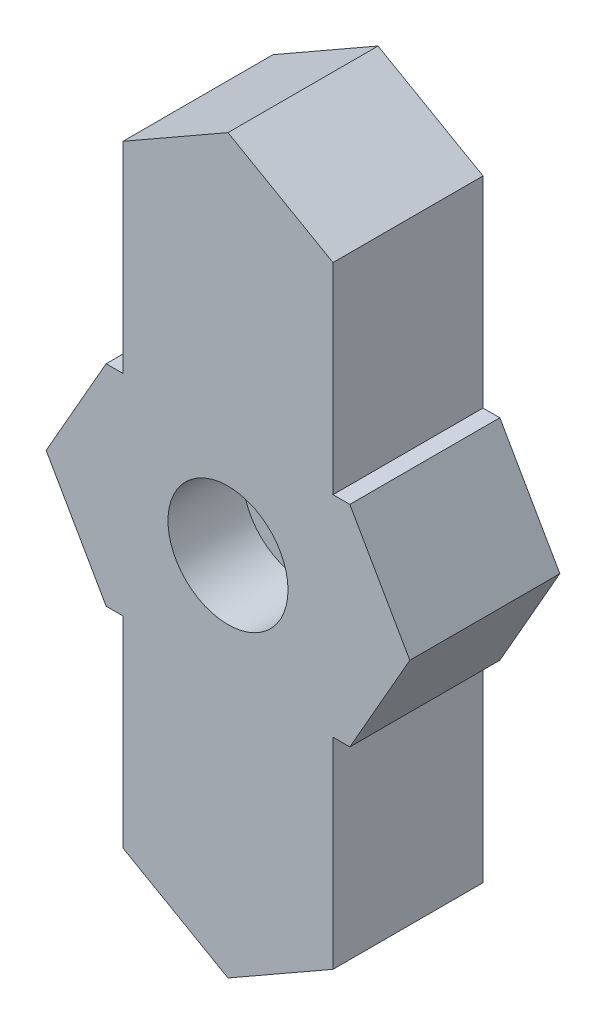
SolidWorks part; units mm, degrees
material "Plain Carbon Steel"
ref_plane "Front Plane" through (0, 0, 0) normal (0, 0, 1) x (1, 0, 0)
ref_plane "Top Plane" through (0, 0, 0) normal (0, 1, 0) x (1, 0, 0)
ref_plane "Right Plane" through (0, 0, 0) normal (1, 0, 0) x (0, 0, -1)
sketch "Sketch1" plane through (0, 0, 0) normal (0, 0, 1) x (1, 0, 0)
  line L0 (0, 0) -> (-15.3924, 0)
  line L8 (0, 30.988) -> (0, 0)
  line L9 (-15.3924, 0) -> (-10.3124, 8.89)
  line L10 (-10.3124, 8.89) -> (-8.89, 8.89)
  line L11 (0, 30.988) -> (-8.89, 25.908)
  line L12 (-8.89, 25.908) -> (-8.89, 8.89)
  point P3 (-7.6962, 0)
  dimension "D1" = 30.988
  dimension "D2" = 15.3924
  dimension "D3" = 8.89
  dimension "D6" = 8.89
extrude "Boss-Extrude1" add sketch "Sketch1" along normal blind 12.7
mirror "Mirror1" about plane through (0, 30.988, 12.7) normal (-1, 0, 0) of "Boss-Extrude1"
mirror "Mirror2" about plane through (0, 0, 12.7) normal (0, 1, 0) of "Mirror1", "Boss-Extrude1"
sketch "Sketch2" plane through (0, 0, 12.7) normal (0, 0, 1) x (1, 0, 0)
  circle A0 centre (0, 0) radius 5.08
  dimension "D1" = 10.16
extrude "Cut-Extrude1" cut sketch "Sketch2" against normal blind 6.35
